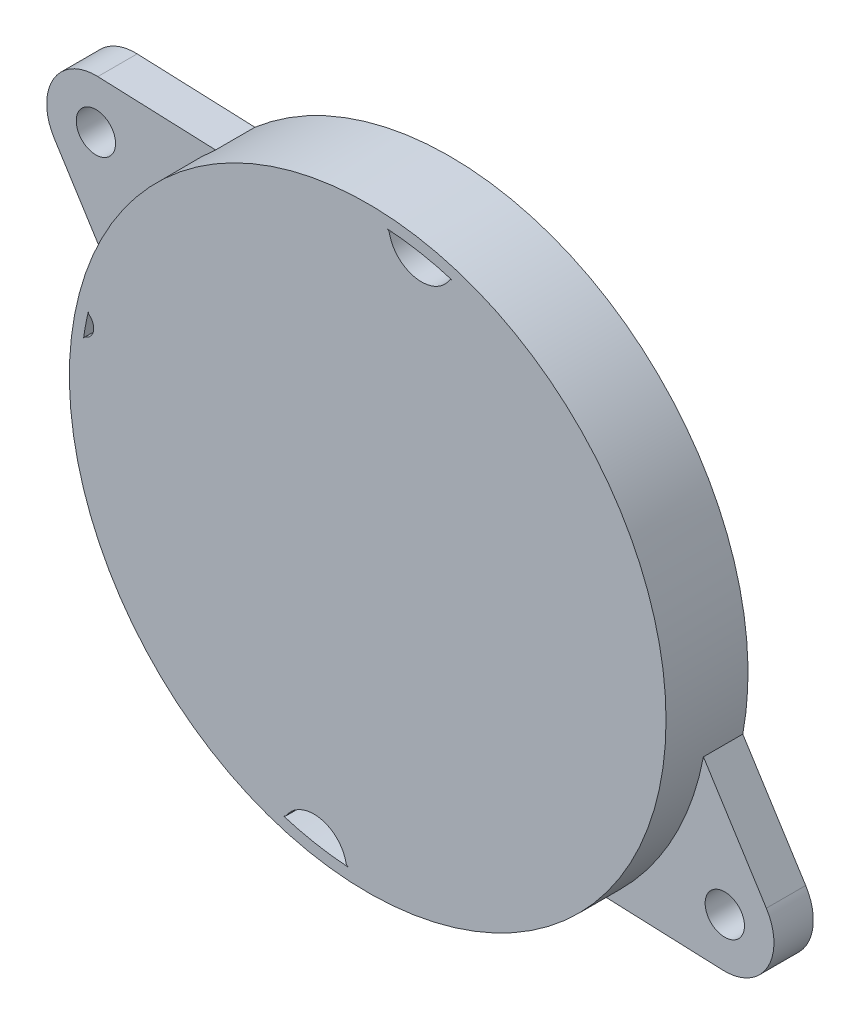
SolidWorks part; units mm, degrees
material "7075-T6, Plate (SS)"
ref_plane "Front" through (0, 0, 0) normal (0, 0, 1) x (1, 0, 0)
ref_plane "Top" through (0, 0, 0) normal (0, 1, 0) x (1, 0, 0)
ref_plane "Right" through (0, 0, 0) normal (1, 0, 0) x (0, 0, -1)
sketch "Sketch4" plane through (0, 0, 0) normal (0, 0, 1) x (1, 0, 0)
  circle A1 centre (0, 0) radius 18.2
  dimension "D1" = 36.4
extrude "Boss-Extrude3" add sketch "Sketch4" along normal blind 5 separate body
sketch "Sketch5" plane through (0, 0, 5) normal (0, 0, 1) x (1, 0, 0)
  line L0 (3.2831, 17.6981) -> (-3.2831, -17.6981) construction
  line L1 (0, 0) -> (9.4774, 0) construction
  line L2 (-17.4671, 3.2402) -> (0, 0) construction
  circle A0 centre (0, 0) radius 18.2 construction
  arc A1 (1.3225, 17.3028) -> (4.9714, 16.6259) centre (3.2831, 17.6981) ccw
  arc A3 (5.1997, 16.7097) -> (1.1395, 17.4629) centre (0, 0) ccw
  arc A5 (5.1997, 16.7097) -> (4.9714, 16.6259) centre (5.1403, 16.5187) ccw
  arc A7 (1.3225, 17.3028) -> (1.1395, 17.4629) centre (1.1265, 17.2633) ccw
  arc A9 (-17.2088, 2.5361) -> (-16.9734, 3.8048) centre (-17.4671, 3.2402) ccw
  arc A11 (-17.0365, 4.0011) -> (-16.9734, 3.8048) centre (-16.8418, 3.9554) ccw
  arc A13 (-17.0365, 4.0011) -> (-17.338, 2.3755) centre (0, 0) ccw
  arc A15 (-17.2088, 2.5361) -> (-17.338, 2.3755) centre (-17.1399, 2.3484) ccw
  arc A17 (-5.1997, -16.7097) -> (-1.1395, -17.4629) centre (0, 0) ccw
  arc A19 (-1.3225, -17.3028) -> (-4.9714, -16.6259) centre (-3.2831, -17.6981) ccw
  arc A21 (-1.3225, -17.3028) -> (-1.1395, -17.4629) centre (-1.1265, -17.2633) ccw
  arc A23 (-5.1997, -16.7097) -> (-4.9714, -16.6259) centre (-5.1403, -16.5187) ccw
  dimension "D1" = 17.5
  dimension "D4" = 2
  dimension "D5" = 0.2
  dimension "D6" = 0.75
  dimension "D2" = 36
  dimension "D3" = 79.491
  dimension "D7" = 17.7651
extrude "Cut-Extrude2" cut sketch "Sketch5" against normal blind 2
sketch "Sketch6" plane through (0, 0, 0) normal (0, 0, 1) x (1, 0, 0)
  line L0 (19.1823, -11.0749) -> (-19.1823, 11.0749) construction
  line L1 (-19.0634, 14.0726) -> (-11.8804, 13.7875)
  line L2 (0, 0) -> (11.8805, 0) construction
  line L3 (-17.8805, 3.395) -> (-21.7189, 9.4731)
  line L4 (0, 0) -> (-4.9124, -8.5085) construction
  line L5 (17.8805, -3.395) -> (21.7189, -9.4731)
  line L7 (19.0634, -14.0726) -> (11.8804, -13.7875)
  circle A0 centre (0, 0) radius 18.2 construction
  arc A1 (-19.0634, 14.0726) -> (-21.7189, 9.4731) centre (-19.1823, 11.0749) ccw
  arc A3 (-11.8804, 13.7875) -> (-17.8805, 3.395) centre (0, 0) ccw
  arc A5 (11.8804, -13.7875) -> (17.8805, -3.395) centre (0, 0) ccw
  arc A7 (19.0634, -14.0726) -> (21.7189, -9.4731) centre (19.1823, -11.0749) ccw
  circle A8 centre (19.1823, -11.0749) radius 1.2
  circle A9 centre (-19.1823, 11.0749) radius 1.2
  point P17 (0, 0)
  dimension "D1" = 2.4
  dimension "D5" = 3
  dimension "D2" = 30
  dimension "D3" = 44.2996
  dimension "D4" = 55.455
extrude "Boss-Extrude4" add sketch "Sketch6" along normal blind 2.4
sketch "Sketch1" plane through (0, 0, 0) normal (0, 0, -1) x (-1, 0, 0)
  circle A0 centre (0, 0) radius 8.25
  arc A1 (11.8804, 13.7875) -> (-17.8805, -3.395) centre (0, 0) ccw construction
  dimension "D1" = 16.5
extrude "Cut-Extrude1" cut sketch "Sketch1" against normal blind 0.2
sketch "Sketch2" plane through (0, 0, 0.2) normal (0, 0, -1) x (-1, 0, 0)
  circle A0 centre (0, 0) radius 8
  circle A1 centre (0, 0) radius 8.25 construction
  dimension "D1" = 16
extrude "Boss-Extrude1" add sketch "Sketch2" along normal blind 1.7
sketch "Sketch3" plane through (0, 0, -1.5) normal (0, 0, -1) x (-1, 0, 0)
  circle A0 centre (0, 0) radius 1.25
  circle A1 centre (0, 0) radius 8 construction
  dimension "D1" = 2.5
extrude "Boss-Extrude2" add sketch "Sketch3" along normal blind 4.5
chamfer "Chamfer1" distance 0.2 angle 45 1 edges at (-1.25, 0, -6)
chamfer "Chamfer2" distance 0.2 angle 45 1 edges at (-8, 0, -1.5)
